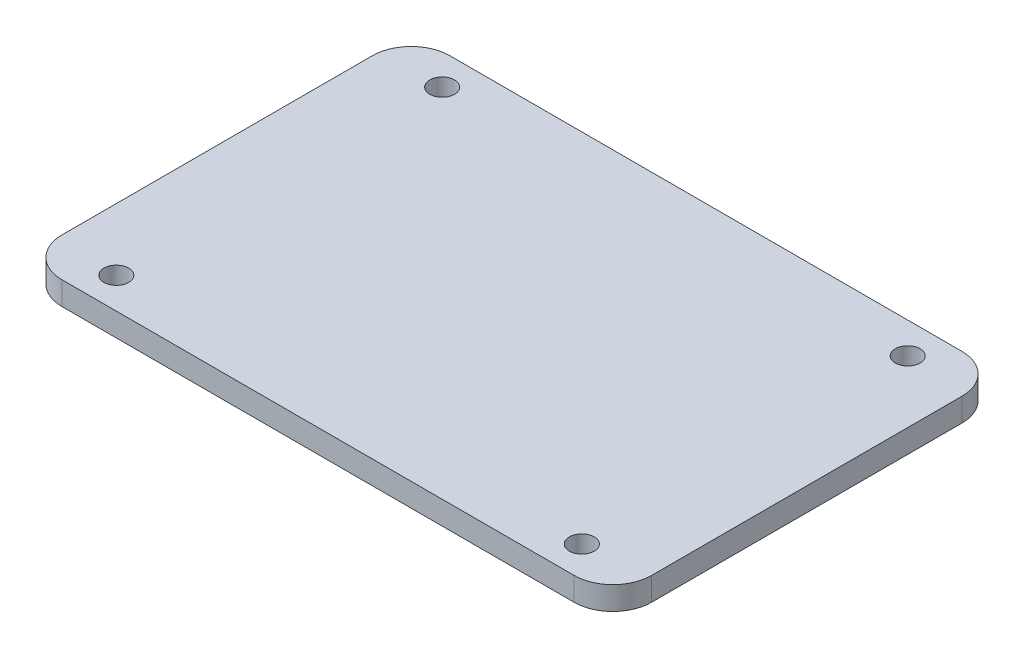
SolidWorks part; units mm, degrees
ref_plane "Front Plane" through (0, 0, 0) normal (0, 0, 1) x (1, 0, 0)
ref_plane "Top Plane" through (0, 0, 0) normal (0, 1, 0) x (1, 0, 0)
ref_plane "Right Plane" through (0, 0, 0) normal (1, 0, 0) x (0, 0, -1)
sketch "Sketch1" plane through (0, 53, 0) normal (0, 1, 0) x (1, 0, 0)
  line L0 (2.5736, 25) -> (-2.5736, 25) construction
  line L1 (33, 25) -> (-33, 25)
  line L2 (-2.5736, -25) -> (2.5736, -25) construction
  line L3 (-33, -25) -> (33, -25)
  line L4 (38, -11.4315) -> (38, 11.4315) construction
  line L5 (38, -20) -> (38, 20)
  line L6 (-38, 11.4315) -> (-38, -11.4315) construction
  line L7 (-38, 20) -> (-38, -20)
  arc A0 (38, 20) -> (33, 25) centre (33, 20) ccw
  arc A1 (33, -25) -> (38, -20) centre (33, -20) ccw
  arc A2 (-33, -25) -> (-38, -20) centre (-33, -20) cw
  arc A3 (-38, 20) -> (-33, 25) centre (-33, 20) cw
  circle A4 centre (30, 21) radius 1.6 construction
  circle A5 centre (30, 21) radius 1.6
  circle A6 centre (-30, 21) radius 1.6 construction
  circle A7 centre (-30, 21) radius 1.6
  circle A8 centre (30, -21) radius 1.6 construction
  circle A9 centre (30, -21) radius 1.6
  circle A10 centre (-30, -21) radius 1.6 construction
  circle A11 centre (-30, -21) radius 1.6
  point P0 (-38, -24.2433)
  point P8 (38, 25)
  point P10 (38.5614, 25)
extrude "Boss-Extrude1" add sketch "Sketch1" along normal blind 3
